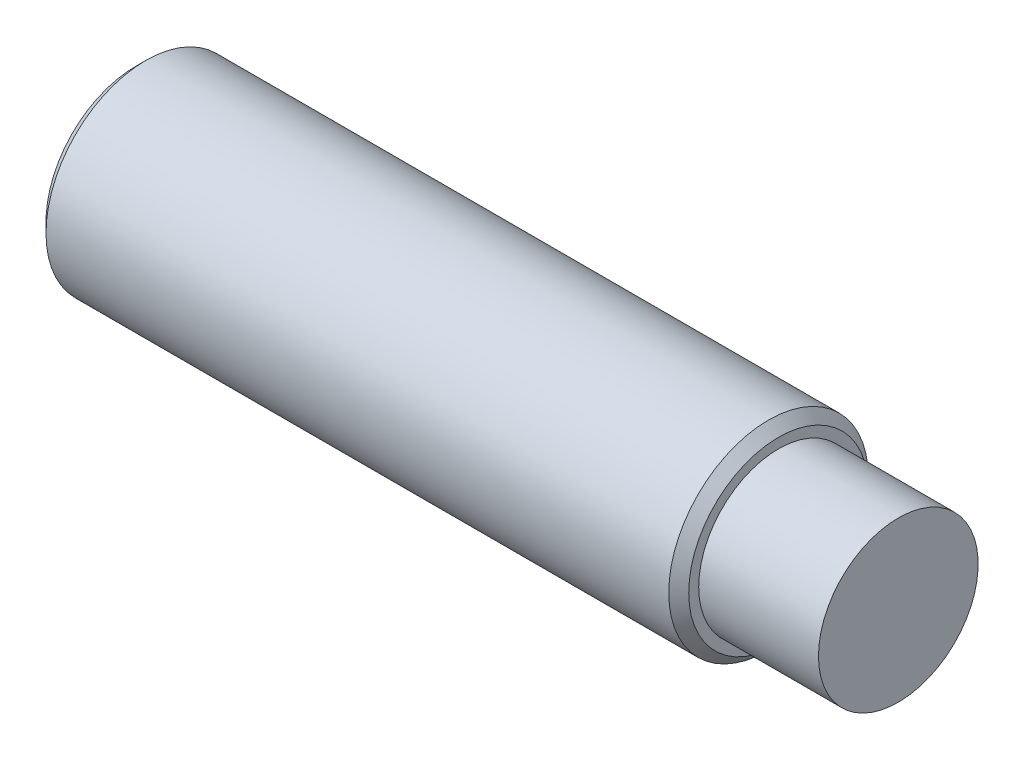
SolidWorks part; units mm, degrees
ref_plane "Front Plane" through (0, 0, 0) normal (0, 0, 1) x (1, 0, 0)
ref_plane "Top Plane" through (0, 0, 0) normal (0, 1, 0) x (1, 0, 0)
ref_plane "Right Plane" through (0, 0, 0) normal (1, 0, 0) x (0, 0, -1)
sketch "Sketch1" plane through (0, 0, 0) normal (0, 0, 1) x (1, 0, 0)
  line L0 (0, 0) -> (0, 5)
  line L1 (0, 5) -> (32.2, 5)
  line L2 (32.2, 5) -> (32.2, 4)
  line L3 (32.2, 4) -> (38.2, 4)
  line L4 (38.2, 4) -> (38.2, 0)
  line L5 (38.2, 0) -> (0, 0)
  line L6 (-21.6251, 0) -> (57.019, 0) construction
  dimension "D1" = 32.2
  dimension "D2" = 6
  dimension "D3" = 10
  dimension "D4" = 8
revolve "Revolve1" add sketch "Sketch1" angle 360 about L6
chamfer "Chamfer1" distance 0.5 angle 45 2 edges at (32.2, 0, 5) (0, 0, 5)
sketch "Sketch6" plane through (0, 0, 0) normal (-1, 0, 0) x (0, 0, 1)
  circle A0 centre (0, 0) radius 3
  dimension "D1" = 6
extrude "Cut-Extrude1" cut sketch "Sketch6" against normal blind 10
